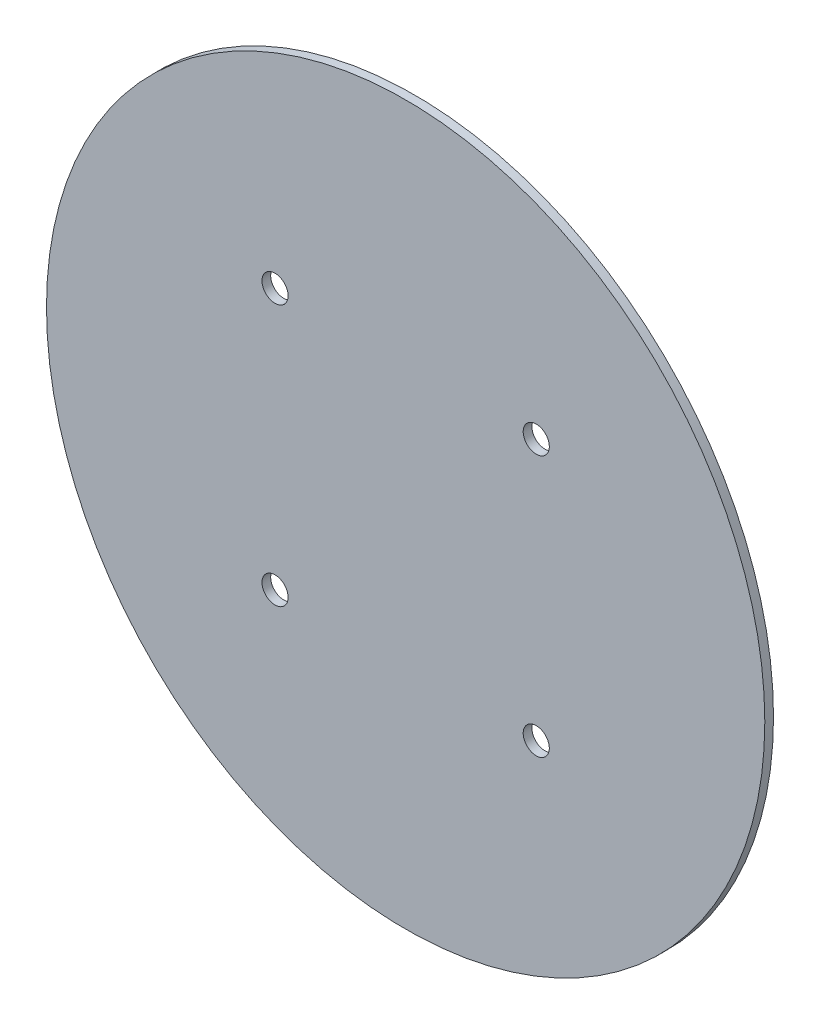
SolidWorks part; units mm, degrees
material "1060 合金"
ref_plane "前视基准面" through (0, 0, 0) normal (0, 0, 1) x (1, 0, 0)
ref_plane "上视基准面" through (0, 0, 0) normal (0, 1, 0) x (1, 0, 0)
ref_plane "右视基准面" through (0, 0, 0) normal (1, 0, 0) x (0, 0, -1)
sketch "草图1" plane through (0, 0, 0) normal (0, 0, 1) x (1, 0, 0)
  circle A0 centre (0, 0) radius 82.5
  dimension "D1" = 165
extrude "凸台-拉伸1" add sketch "草图1" along normal blind 2
sketch "草图2" plane through (0, 0, 2) normal (0, 0, 1) x (1, 0, 0)
  line L0 (0, 30) -> (0, 0) construction
  line L1 (0, 0) -> (0, -30) construction
  line L2 (-34, 0) -> (0, 0) construction
  line L3 (0, 0) -> (30, 0) construction
  circle A4 centre (30, 30) radius 3
  circle A5 centre (-30, 30) radius 3
  circle A6 centre (-30, -30) radius 3
  circle A7 centre (30, -30) radius 3
  dimension "D1" = 6
  dimension "D2" = 6
  dimension "D3" = 6
  dimension "D4" = 6
  dimension "D5" = 60
  dimension "D6" = 60
extrude "切除-拉伸1" cut sketch "草图2" against normal through all
